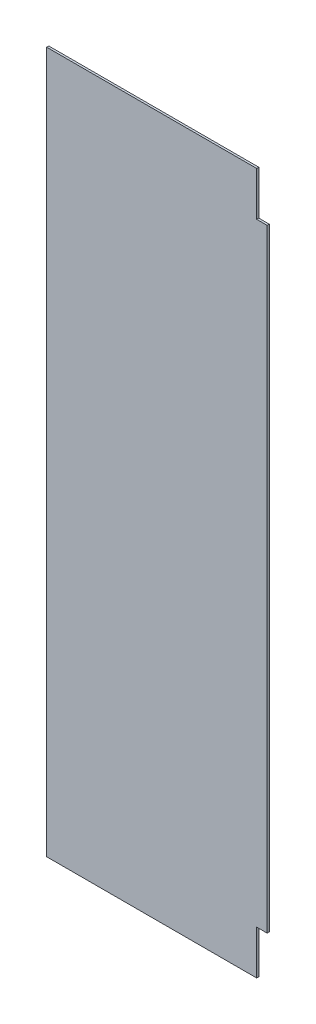
SolidWorks part; units mm, degrees
ref_plane "Спереди" through (0, 0, 0) normal (0, 0, 1) x (1, 0, 0)
ref_plane "Сверху" through (0, 0, 0) normal (0, 1, 0) x (1, 0, 0)
ref_plane "Справа" through (0, 0, 0) normal (1, 0, 0) x (0, 0, -1)
sketch "Эскиз1" plane through (0, 0, 0) normal (0, 0, 1) x (1, 0, 0)
  line L0 (23.4, 14.6) -> (23.9, 14.6)
  line L1 (13.4, -16.7) -> (23.4, -16.7)
  line L2 (13.4, -16.7) -> (13.4, 16.7)
  line L3 (13.4, 16.7) -> (23.4, 16.7)
  line L4 (23.4, -16.7) -> (23.4, -14.6)
  line L5 (13.4, -16.7) -> (23.4, 16.7) construction
  line L6 (13.4, 16.7) -> (23.4, -16.7) construction
  line L7 (23.9, -14.8) -> (23.9, 14.8) construction
  line L8 (23.9, 14.6) -> (23.9, -14.6)
  line L9 (-23.6, 17) -> (23.4, 17) construction
  line L10 (23.4, 17) -> (23.4, 14.8) construction
  line L11 (23.9, -14.6) -> (23.4, -14.6)
  line L12 (23.4, 14.6) -> (23.4, 16.7)
  line L13 (23.4, 14.8) -> (23.9, 14.8) construction
  point P0 (18.4, 0)
  point P14 (23.9, 0)
  dimension "D1" = 10
  dimension "D2" = 0.3
  dimension "D3" = 0.2
extrude "Бобышка-Вытянуть1" add sketch "Эскиз1" along normal blind 0.1
